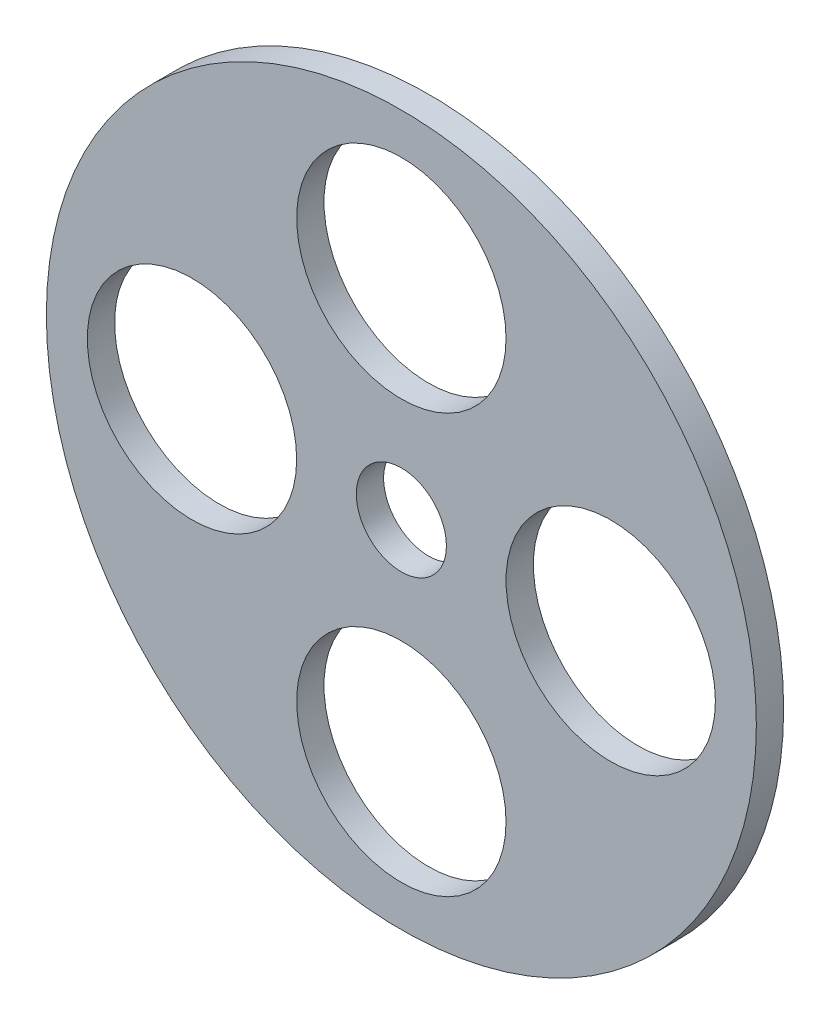
SolidWorks part; units mm, degrees
material "Plywood"
ref_plane "Plan de face" through (0, 0, 0) normal (0, 0, 1) x (1, 0, 0)
ref_plane "Plan de dessus" through (0, 0, 0) normal (0, 1, 0) x (1, 0, 0)
ref_plane "Plan de droite" through (0, 0, 0) normal (1, 0, 0) x (0, 0, -1)
sketch "Esquisse1" plane through (0, 0, 0) normal (0, 0, 1) x (1, 0, 0)
  line L0 (0, 0) -> (0, 23) construction
  circle A0 centre (0, 0) radius 39
  circle A1 centre (0, 0) radius 4.95
  circle A2 centre (0, 23) radius 11.5
  circle A3 centre (23, 0) radius 11.5
  circle A4 centre (0, -23) radius 11.5
  circle A5 centre (-23, 0) radius 11.5
  point P15 (0, 0)
  dimension "D1" = 9.9
  dimension "D2" = 78
  dimension "D3" = 23
  dimension "D4" = 23
  dimension "D5" = 4
extrude "Boss.-Extru.1" add sketch "Esquisse1" along normal blind 3
